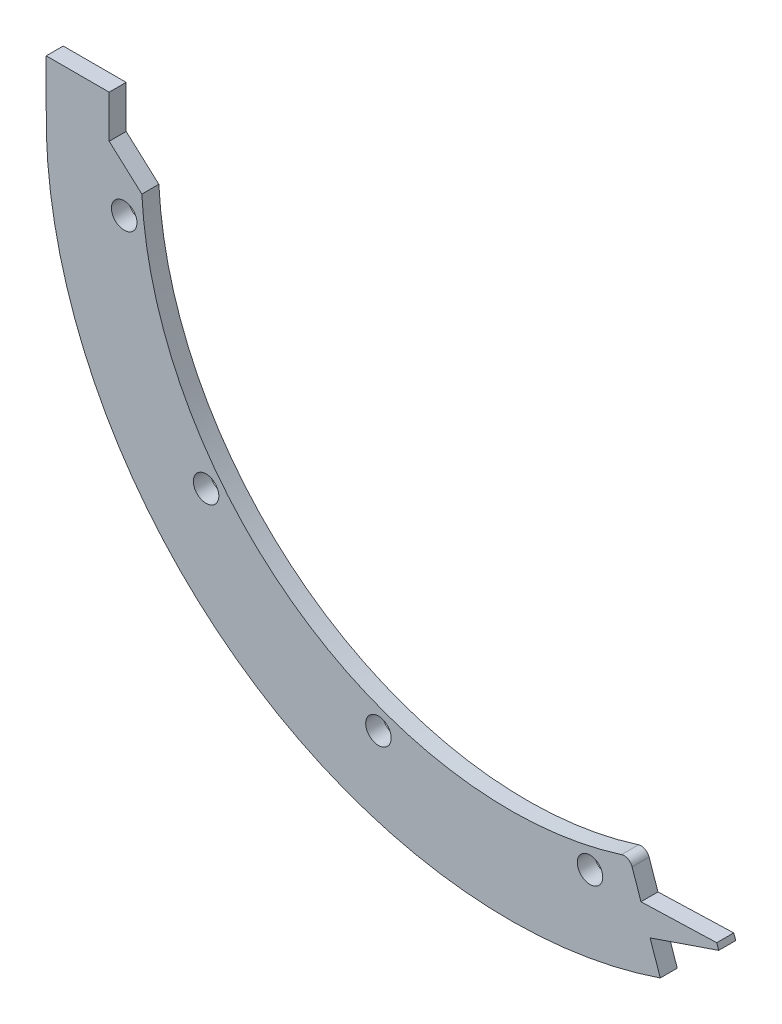
SolidWorks part; units mm, degrees
ref_plane "前视基准面" through (0, 0, 0) normal (0, 0, 1) x (1, 0, 0)
ref_plane "上视基准面" through (0, 0, 0) normal (0, 1, 0) x (1, 0, 0)
ref_plane "右视基准面" through (0, 0, 0) normal (1, 0, 0) x (0, 0, -1)
sketch "Sketch1" plane through (0, 0, 0) normal (0, 0, 1) x (1, 0, 0)
  line L18 (22.5089, -130.6992) -> (13.5977, -130.9838)
  line L19 (22.7495, -131.3629) -> (22.5089, -130.6992)
  line L20 (14.6737, -134.1273) -> (22.7495, -131.3629)
  line L21 (15.8677, -137.6154) -> (14.6737, -134.1273)
  line L22 (-56.3425, -79.8) -> (-56.3425, -84.8)
  line L23 (-48.9405, -79.8) -> (-56.3425, -79.8)
  line L24 (-48.9405, -84.8) -> (-48.9405, -79.8)
  line L25 (-45.0968, -88.2603) -> (-48.9405, -84.8)
  line L26 (13.5977, -130.9838) -> (12.5607, -127.9544)
  arc A6 (-56.3425, -84.8) -> (15.8677, -137.6154) centre (-1.8002, -86) ccw
  arc A7 (-45.0968, -88.2603) -> (11.3122, -127.3251) centre (-1.8002, -86) ccw
  arc A8 (12.5607, -127.9544) -> (11.3122, -127.3251) centre (11.6146, -128.2783) ccw
  circle A10 centre (7.6073, -130.7228) radius 1.5
  circle A11 centre (-37.5439, -114.4784) radius 1.5
  circle A12 centre (-47.1727, -91.4738) radius 1.5
  circle A13 centre (-17.2718, -129.003) radius 1.5
extrude "Boss-Extrude1" add sketch "Sketch1" along normal blind 2
